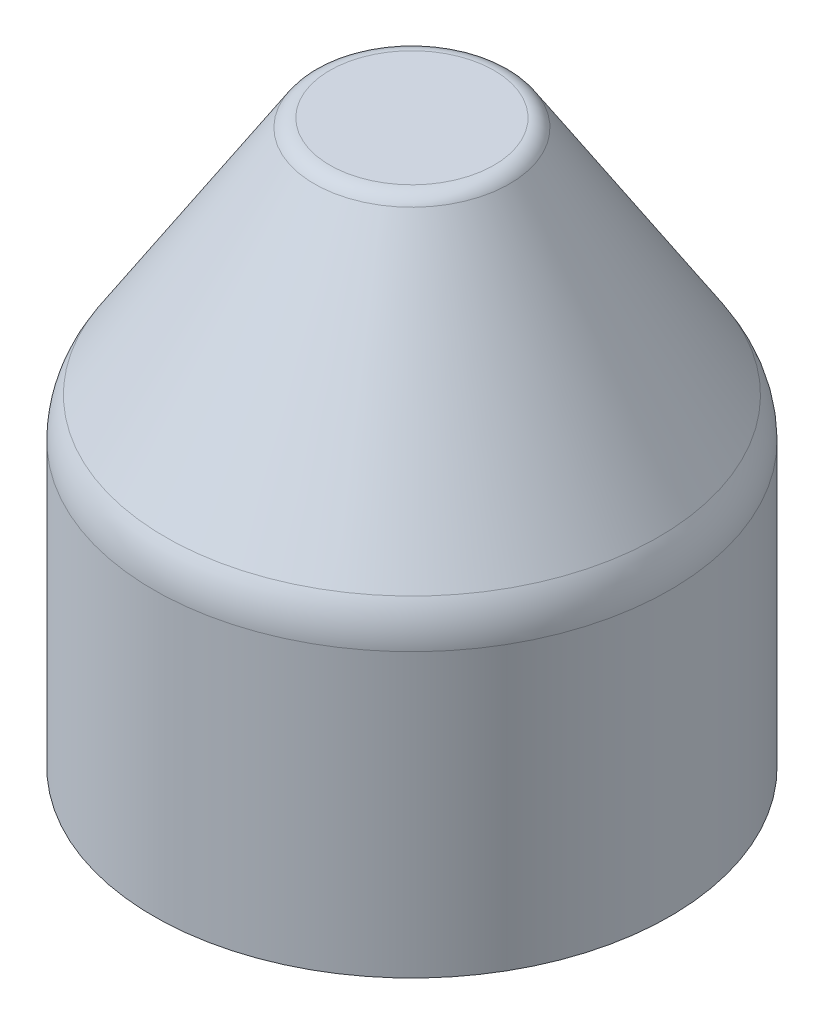
SolidWorks part; units mm, degrees
material "Nitrile Rubber"
ref_plane "Front Plane" through (0, 0, 0) normal (0, 0, 1) x (1, 0, 0)
ref_plane "Top Plane" through (0, 0, 0) normal (0, 1, 0) x (1, 0, 0)
ref_plane "Right Plane" through (0, 0, 0) normal (1, 0, 0) x (0, 0, -1)
sketch "Sketch1" plane through (0, 0, 0) normal (0, 0, 1) x (1, 0, 0)
  line L0 (0, 0) -> (0, 76.8127) construction
  line L1 (0, 32) -> (4.454, 32)
  line L2 (5.2952, 31.5408) -> (13.3647, 18.9882)
  line L3 (14, 16.8252) -> (14, 1.5)
  line L4 (10.75, 0) -> (10, 0)
  line L5 (10, 0) -> (10, 16)
  line L6 (3.8, 30) -> (0, 30)
  line L7 (0, 30) -> (0, 32)
  line L8 (3.8, 30) -> (3.8, 16)
  line L9 (3.8, 16) -> (10, 16)
  line L10 (10.75, 0) -> (14, 1.5)
  arc A0 (4.454, 32) -> (5.2952, 31.5408) centre (4.454, 31) cw
  arc A1 (13.3647, 18.9882) -> (14, 16.8252) centre (10, 16.8252) cw
  point P16 (14, 18)
  point P17 (5, 32)
  dimension "D9" = 1
  dimension "D10" = 4
  dimension "D1" = 20
  dimension "D2" = 32
  dimension "D3" = 30
  dimension "D4" = 7.6
  dimension "D5" = 16
  dimension "D6" = 28
  dimension "D7" = 18
  dimension "D8" = 10
  dimension "D11" = 21.5
  dimension "D12" = 1.5
revolve "Revolve1" add sketch "Sketch1" angle 360 about L0
